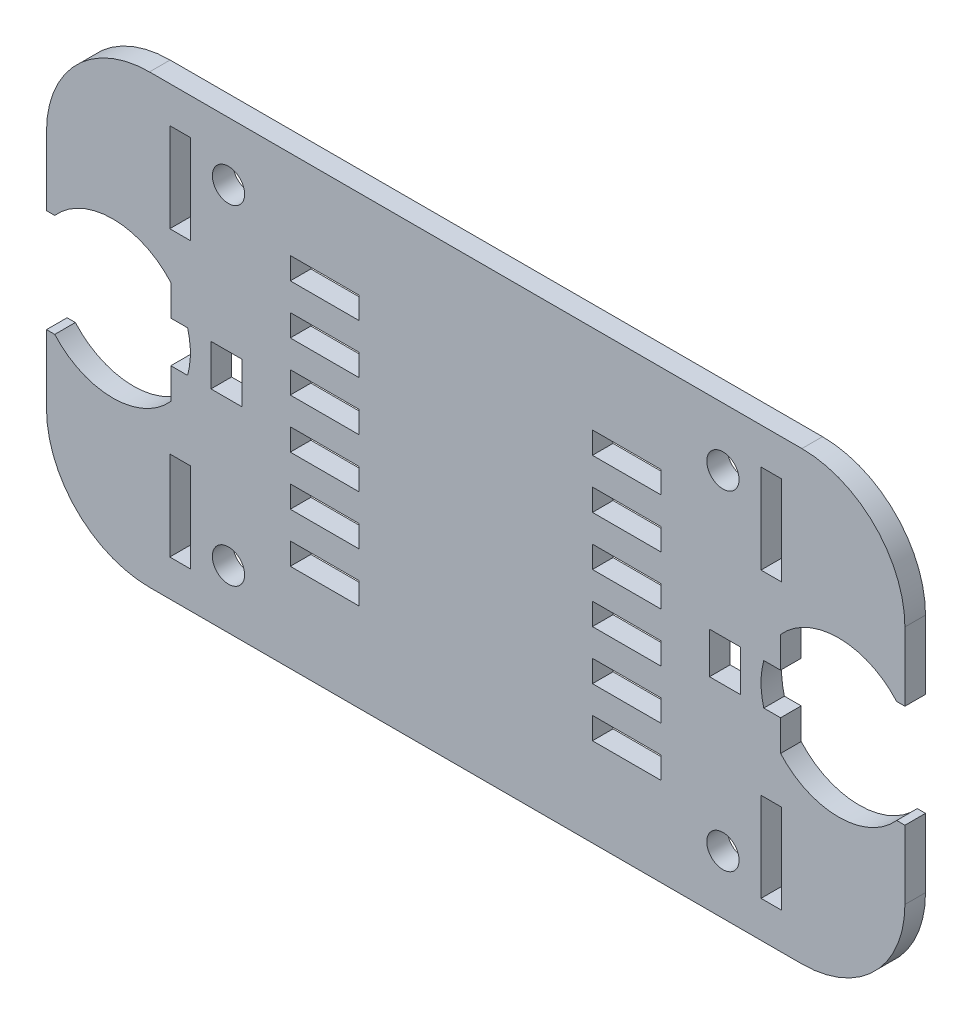
SolidWorks part; units mm, degrees
ref_plane "Přední rovina" through (0, 0, 0) normal (0, 0, 1) x (1, 0, 0)
ref_plane "Horní rovina" through (0, 0, 0) normal (0, 1, 0) x (1, 0, 0)
ref_plane "Pravá rovina" through (0, 0, 0) normal (1, 0, 0) x (0, 0, -1)
sketch "Skica2" plane through (0, 0, 0) normal (0, 0, 1) x (1, 0, 0)
  line L0 (-39.6595, 0) -> (1943.3131, 0) construction
  line L1 (0, -39.6595) -> (0, 1943.3131) construction
  line L2 (-62.5, 7.5) -> (-61.3, 7.5)
  line L3 (-44.3956, 7.5) -> (-44.3956, 3)
  line L4 (-44.3956, -3) -> (-44.3956, -7.5)
  line L5 (-61.3, -7.5) -> (-62.5, -7.5)
  line L6 (-41.5478, 14.2) -> (-41.5478, -3) construction
  line L7 (-62.5, 32.5) -> (62.5, 32.5)
  line L8 (-62.5, 32.5) -> (-62.5, -32.5) construction
  line L9 (-62.5, -32.5) -> (62.5, -32.5)
  line L10 (62.5, 32.5) -> (62.5, -32.5) construction
  line L11 (-62.5, 32.5) -> (62.5, -32.5) construction
  line L12 (-62.5, -32.5) -> (62.5, 32.5) construction
  line L13 (-38.5478, -3) -> (-34.0478, -3)
  line L14 (-38.5478, -3) -> (-38.5478, 3)
  line L15 (-38.5478, 3) -> (-34.0478, 3)
  line L16 (-34.0478, -3) -> (-34.0478, 3)
  line L17 (-38.5478, -3) -> (-34.0478, 3) construction
  line L18 (-38.5478, 3) -> (-34.0478, -3) construction
  line L19 (-44.5478, -14.2) -> (-41.5478, -14.2)
  line L20 (-44.5478, 27.2) -> (-41.5478, 27.2)
  line L21 (-44.5478, 27.2) -> (-44.5478, 14.2)
  line L22 (-44.5478, 14.2) -> (-41.5478, 14.2)
  line L23 (-41.5478, 27.2) -> (-41.5478, 14.2)
  line L24 (-44.5478, -27.2) -> (-44.5478, -14.2)
  line L25 (-44.5478, -27.2) -> (-41.5478, -27.2)
  line L26 (-41.5478, -27.2) -> (-41.5478, -14.2)
  line L27 (-62.5, 7.5) -> (-62.5, 32.5)
  line L28 (-62.5, -7.5) -> (-62.5, -32.5)
  line L29 (44.5478, -27.2) -> (41.5478, -27.2)
  line L30 (44.5478, -27.2) -> (44.5478, -14.2)
  line L31 (41.5478, -27.2) -> (41.5478, -14.2)
  line L32 (44.5478, -14.2) -> (41.5478, -14.2)
  line L33 (44.5478, 14.2) -> (41.5478, 14.2)
  line L34 (44.5478, 27.2) -> (41.5478, 27.2)
  line L35 (41.5478, 27.2) -> (41.5478, 14.2)
  line L36 (44.5478, 27.2) -> (44.5478, 14.2)
  line L37 (34.0478, -3) -> (34.0478, 3)
  line L38 (38.5478, -3) -> (34.0478, -3)
  line L39 (38.5478, -3) -> (38.5478, 3)
  line L40 (38.5478, 3) -> (34.0478, 3)
  line L41 (44.3956, -3) -> (44.3956, -7.5)
  line L42 (44.3956, 7.5) -> (44.3956, 3)
  line L43 (61.3, -7.5) -> (62.5, -7.5)
  line L44 (62.5, 7.5) -> (61.3, 7.5)
  line L45 (62.5, -7.5) -> (62.5, -32.5)
  line L46 (62.5, 7.5) -> (62.5, 32.5)
  line L47 (-44.3956, 3) -> (-41.9533, 3)
  line L48 (-44.3956, -3) -> (-41.9533, -3)
  line L49 (44.3956, -3) -> (41.9533, -3)
  line L50 (44.3956, 3) -> (41.9533, 3)
  line L56 (-27, 19.6) -> (-17, 19.6)
  line L57 (-27, 19.6) -> (-27, 16.4)
  line L58 (-27, 16.4) -> (-17, 16.4)
  line L59 (-17, 19.6) -> (-17, 16.4)
  line L63 (-27, 12.4) -> (-17, 12.4)
  line L64 (-27, 12.4) -> (-27, 9.2)
  line L65 (-27, 9.2) -> (-17, 9.2)
  line L66 (-17, 12.4) -> (-17, 9.2)
  line L71 (-27, 5.2) -> (-17, 5.2)
  line L72 (-27, 5.2) -> (-27, 2)
  line L73 (-27, 2) -> (-17, 2)
  line L74 (-17, 5.2) -> (-17, 2)
  line L87 (-17, -5.2) -> (-17, -2)
  line L88 (-27, -2) -> (-17, -2)
  line L89 (-27, -5.2) -> (-27, -2)
  line L90 (-27, -5.2) -> (-17, -5.2)
  line L91 (-17, -12.4) -> (-17, -9.2)
  line L92 (-27, -9.2) -> (-17, -9.2)
  line L93 (-27, -12.4) -> (-27, -9.2)
  line L94 (-27, -12.4) -> (-17, -12.4)
  line L95 (-27, -16.4) -> (-17, -16.4)
  line L96 (-17, -19.6) -> (-17, -16.4)
  line L97 (-27, -19.6) -> (-27, -16.4)
  line L98 (-27, -19.6) -> (-17, -19.6)
  line L99 (27, -19.6) -> (17, -19.6)
  line L100 (27, -19.6) -> (27, -16.4)
  line L101 (27, -16.4) -> (17, -16.4)
  line L102 (17, -19.6) -> (17, -16.4)
  line L103 (27, -12.4) -> (17, -12.4)
  line L104 (27, -12.4) -> (27, -9.2)
  line L105 (27, -9.2) -> (17, -9.2)
  line L106 (17, -12.4) -> (17, -9.2)
  line L107 (17, -5.2) -> (17, -2)
  line L108 (27, -5.2) -> (17, -5.2)
  line L109 (27, -5.2) -> (27, -2)
  line L110 (27, -2) -> (17, -2)
  line L111 (17, 5.2) -> (17, 2)
  line L112 (27, 2) -> (17, 2)
  line L113 (27, 5.2) -> (27, 2)
  line L114 (27, 5.2) -> (17, 5.2)
  line L115 (27, 9.2) -> (17, 9.2)
  line L116 (27, 12.4) -> (27, 9.2)
  line L117 (27, 12.4) -> (17, 12.4)
  line L118 (17, 12.4) -> (17, 9.2)
  line L119 (27, 16.4) -> (17, 16.4)
  line L120 (27, 19.6) -> (27, 16.4)
  line L121 (17, 19.6) -> (17, 16.4)
  line L122 (27, 19.6) -> (17, 19.6)
  arc A0 (-44.3956, 7.5) -> (-61.3, 7.5) centre (-52.8478, 0) ccw
  arc A2 (-61.3, -7.5) -> (-44.3956, -7.5) centre (-52.8478, 0) ccw
  circle A3 centre (-52.8478, 0) radius 11.3 construction
  arc A5 (44.3956, 7.5) -> (61.3, 7.5) centre (52.8478, 0) cw
  arc A6 (61.3, -7.5) -> (44.3956, -7.5) centre (52.8478, 0) cw
  arc A19 (-41.9533, 3) -> (-41.9533, -3) centre (-52.8478, 0) cw
  arc A20 (41.9533, 3) -> (41.9533, -3) centre (52.8478, 0) ccw
  circle A21 centre (-36, 24) radius 2.35
  circle A22 centre (36, 24) radius 2.35
  circle A23 centre (-36, -24) radius 2.35
  circle A24 centre (36, -24) radius 2.35
  point P15 (-36.2978, 0)
  point P26 (0, 0)
  dimension "D1" = 22.6
  dimension "D2" = 6
  dimension "D17" = 72
  dimension "D19" = 17
  dimension "D13" = 36
  dimension "D15" = 24
  dimension "D3" = 15
  dimension "D4" = 1.2
  dimension "D5" = 125
  dimension "D6" = 65
  dimension "D7" = 6
  dimension "D8" = 4.5
  dimension "D9" = 3
  dimension "D10" = 13
  dimension "D11" = 3
  dimension "D12" = 14.2
  dimension "D14" = 36
  dimension "D16" = 24
  dimension "D18" = 24
  dimension "D20" = 10
  dimension "D21" = 3.2
  dimension "D22" = 2
  dimension "D23" = 4
  dimension "D24" = 4
  dimension "D25" = 3.2
  dimension "D26" = 3.2
  dimension "D27" = 17
  dimension "D28" = 17
  dimension "D29" = 10
  dimension "D30" = 10
  dimension "D31" = 5.5478
  dimension "D32" = 5.5478
extrude "Přidat vysunutím1" add sketch "Skica2" along normal blind 3
fillet "Zaoblit1" radius 15 4 edges at (62.5, -32.5, 1.5) (-62.5, -32.5, 1.5) (62.5, 32.5, 1.5) (-62.5, 32.5, 1.5)
